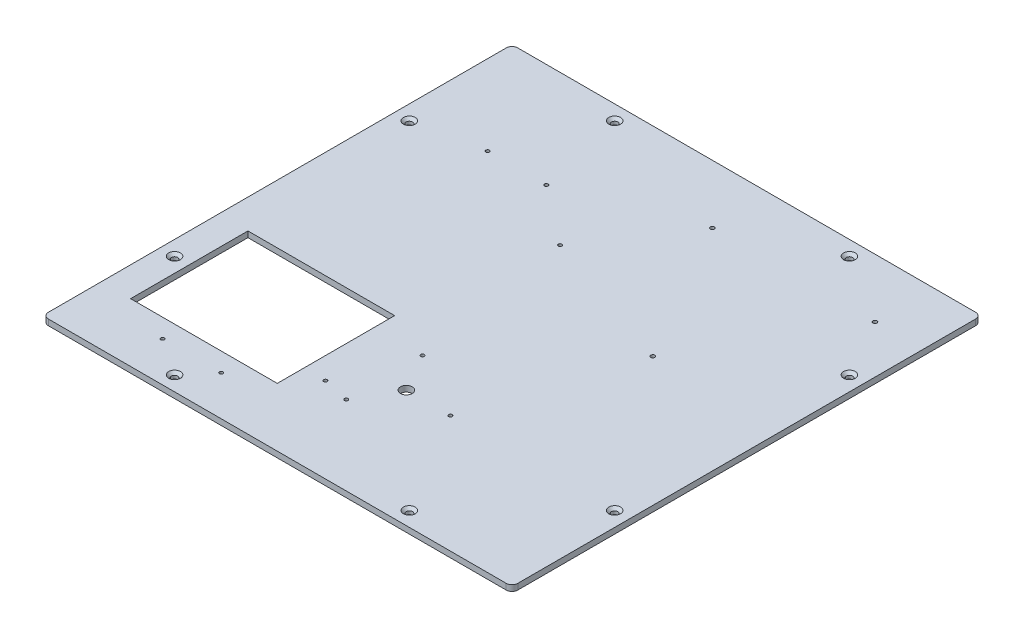
SolidWorks part; units mm, degrees
ref_plane "Front Plane" through (0, 0, 0) normal (0, 0, 1) x (1, 0, 0)
ref_plane "Top Plane" through (0, 0, 0) normal (0, 1, 0) x (1, 0, 0)
ref_plane "Right Plane" through (0, 0, 0) normal (1, 0, 0) x (0, 0, -1)
sketch "Sketch1" plane through (0, 0, 0) normal (0, 1, 0) x (1, 0, 0)
  line L1 (-400, -400) -> (400, -400)
  line L2 (-400, -400) -> (-400, 400)
  line L3 (-400, 400) -> (400, 400)
  line L4 (400, -400) -> (400, 400)
  line L5 (-400, -400) -> (400, 400) construction
  line L6 (-400, 400) -> (400, -400) construction
  point P0 (0, 0)
  dimension "D1" = 800
extrude "Boss-Extrude1" add sketch "Sketch1" along normal blind 10
fillet "Fillet1" radius 10 4 edges at (-400, 5, 400) (-400, 5, -400) (400, 5, -400) (400, 5, 400)
sketch "Sketch2" plane through (0, 10, 0) normal (0, 1, 0) x (1, 0, 0)
  line L0 (-400, 390) -> (-400, -390) construction
  line L1 (-350, -100) -> (-100, -100)
  line L2 (-350, -100) -> (-350, -300)
  line L3 (-350, -300) -> (-100, -300)
  line L4 (-100, -100) -> (-100, -300)
  line L6 (-100, -200) -> (20, -200) construction
  line L7 (-350, -200) -> (-400, -200) construction
  line L8 (-390, -400) -> (390, -400) construction
  circle A0 centre (20, -200) radius 10
  dimension "D5" = 20
  dimension "D1" = 50
  dimension "D2" = 250
  dimension "D3" = 200
  dimension "D4" = 200
  dimension "D6" = 120
extrude "Cut-Extrude1" cut sketch "Sketch2" against normal through all both and the other way through all
sketch "Sketch4" plane through (0, 10, 0) normal (0, 1, 0) x (1, 0, 0)
  line L0 (-200, 375) -> (200, 375) construction
  line L1 (375, 200) -> (375, -200) construction
  line L2 (200, -375) -> (-200, -375) construction
  line L3 (-375, -200) -> (-375, 200) construction
  line L4 (0, 375) -> (0, 400) construction
  line L5 (390, 400) -> (-390, 400) construction
  line L6 (-375, 0) -> (-400, 0) construction
  line L7 (-400, 390) -> (-400, -390) construction
  line L8 (375, 0) -> (400, 0) construction
  line L9 (400, -390) -> (400, 390) construction
  line L10 (0, -375) -> (0, -400) construction
  line L11 (-390, -400) -> (390, -400) construction
  circle A0 centre (-200, 375) radius 6
  circle A1 centre (-375, 200) radius 6
  circle A2 centre (-375, -200) radius 6
  circle A3 centre (-200, -375) radius 6
  circle A4 centre (200, -375) radius 6
  circle A5 centre (375, -200) radius 6
  circle A6 centre (375, 200) radius 6
  circle A7 centre (200, 375) radius 6
  point P0 (-200, 375)
  point P1 (200, 375)
  point P2 (375, 200)
  point P3 (375, -200)
  point P4 (200, -375)
  point P5 (-200, -375)
  point P6 (-375, -200)
  point P7 (-375, 200)
  point P49 (-200, -375)
  point P52 (200, -375)
  point P54 (375, -200)
  point P56 (375, 200)
  point P62 (-375, 200)
  point P64 (-375, -200)
  point P66 (-200, 375)
  point P70 (200, 375)
  dimension "D3" = 12
  dimension "D1" = 25
  dimension "D2" = 400
sketch "Sketch6" plane through (0, 10, 0) normal (0, 1, 0) x (1, 0, 0)
  line L0 (95, -200) -> (-17.5, -135.0481) construction
  line L1 (-17.5, -135.0481) -> (-17.5, -264.9519) construction
  line L2 (-17.5, -264.9519) -> (95, -200) construction
  circle A0 centre (20, -200) radius 75 construction
  circle A1 centre (-17.5, -135.0481) radius 3
  circle A2 centre (-17.5, -264.9519) radius 3
  circle A3 centre (95, -200) radius 3
  dimension "D1" = 150
  dimension "D2" = 6
extrude "Cut-Extrude5" cut sketch "Sketch6" against normal through all both and the other way through all
sketch "Sketch5" plane through (0, 10, 0) normal (0, 1, 0) x (1, 0, 0)
  line L0 (95, -200) -> (-17.5, -135.0481) construction
  line L1 (-17.5, -135.0481) -> (-17.5, -264.9519) construction
  line L2 (-17.5, -264.9519) -> (95, -200) construction
  circle A0 centre (20, -200) radius 75 construction
  circle A1 centre (-17.5, -135.0481) radius 6
  circle A2 centre (-17.5, -264.9519) radius 6
  circle A3 centre (95, -200) radius 6
  dimension "D1" = 150
  dimension "D2" = 12
extrude "Cut-Extrude4" [suppressed] cut sketch "Sketch5" against normal through all both and the other way through all
sketch "Sketch7" plane through (0, 0, 0) normal (0, -1, 0) x (1, 0, 0)
  circle A0 centre (-263.5, 332) radius 3
  circle A1 centre (-163.5, 332) radius 3
  circle A2 centre (-63, 255) radius 3
  circle A3 centre (-63, -145) radius 3
  circle A4 centre (-163.5, -222) radius 3
  circle A5 centre (-263.5, -222) radius 3
  dimension "D1" = 6
extrude "Cut-Extrude6" cut sketch "Sketch7" against normal through all both and the other way through all
sketch "Sketch8" plane through (0, 10, 0) normal (0, 1, 0) x (1, 0, 0)
  line L0 (20, -200) -> (20, 220) construction
  line L1 (20, 220) -> (180, 220) construction
  line L2 (180, 60) -> (318.5641, 300) construction
  line L3 (318.5641, 300) -> (41.4359, 300) construction
  line L4 (41.4359, 300) -> (180, 60) construction
  circle A0 centre (180, 220) radius 160 construction
  point P5 (41.4359, 300)
  point P7 (318.5641, 300)
  point P9 (180, 60)
  point P19 (41.4359, 300)
  point P21 (318.5641, 300)
  point P23 (180, 60)
  dimension "D2" = 320
  dimension "D1" = 160
  dimension "D3" = 420
hole_wizard "CSK for M10 Countersunk Flat Head Screw2" positions "Sketch4" profile "Sketch12" countersink size "M10" standard "ISO" end condition through all
sketch "Sketch12" plane through (200, 10, -375) normal (1, 0, 0) x (0, 0, 1)
  line L0 (0, 0) -> (0, 10)
  line L1 (0, 10) -> (5.5, 10)
  line L2 (5.5, 10) -> (5.5, 4.5)
  line L3 (5.5, 4.5) -> (10, 0)
  line L5 (10, 0) -> (0, 0)
  line L6 (-5.5, 4.5) -> (-10, 0) construction
  line L11 (0, -6.35) -> (0, 107.95) construction
  dimension "Thru Hole Dia." = 11
  dimension "Thru Hole Depth" = 10
  dimension "Near C'Sink Dia." = 20
  dimension "Near C'Sink Angle" = 90
hole_wizard "M8 Tapped Hole2" positions "Sketch8" profile "Sketch13" tap size "M8" standard "ISO" end condition through all
sketch "Sketch13" plane through (180, 10, -60) normal (1, 0, 0) x (0, 0, 1)
  line L0 (0, 0) -> (0, 10)
  line L1 (0, 10) -> (3.4, 10)
  line L2 (3.4, 10) -> (3.4, 0)
  line L5 (3.4, 0) -> (0, 0)
  line L11 (0, -6.35) -> (0, 107.95) construction
  dimension "Thru Tap Drill Dia." = 6.8
  dimension "Thru Tap Drill Depth" = 10
cosmetic thread "Hole Thread1" parameters "D2"=8
cosmetic thread "Hole Thread2" parameters "D2"=8
cosmetic thread "Hole Thread3" parameters "D2"=8
